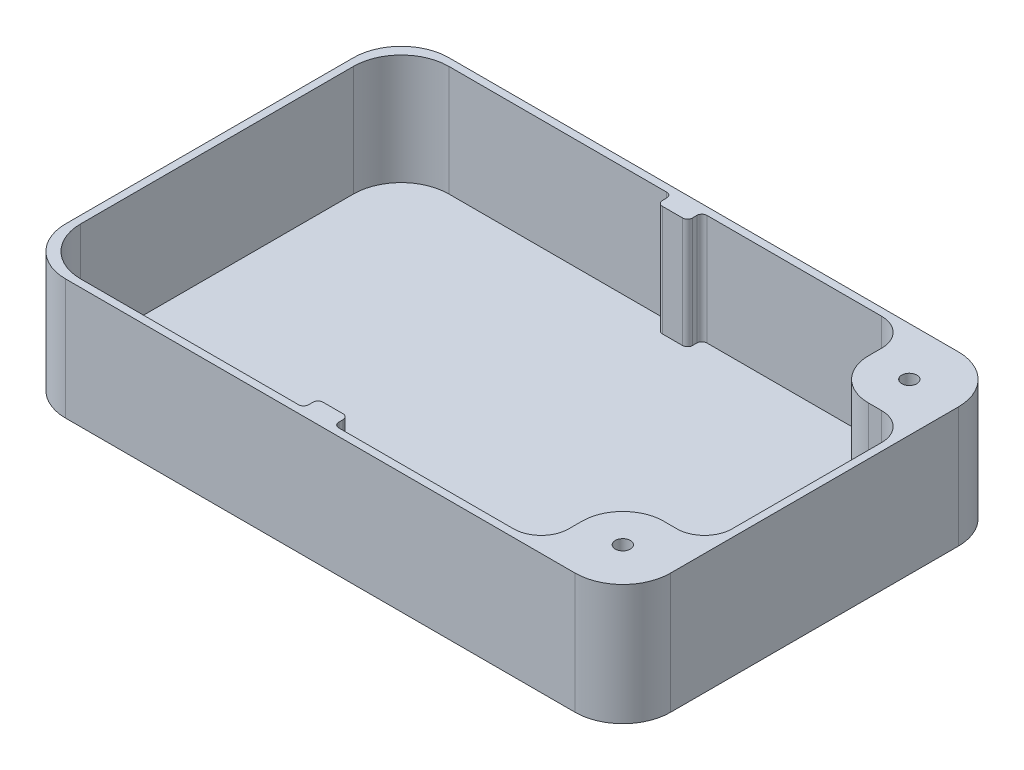
SolidWorks part; units mm, degrees
ref_plane "Front Plane" through (0, 0, 0) normal (0, 0, 1) x (1, 0, 0)
ref_plane "Top Plane" through (0, 0, 0) normal (0, 1, 0) x (1, 0, 0)
ref_plane "Right Plane" through (0, 0, 0) normal (1, 0, 0) x (0, 0, -1)
sketch "Sketch1" plane through (0, 0, 0) normal (0, 1, 0) x (1, 0, 0)
  line L1 (-60.2, 38.14) -> (60.2, 38.14)
  line L2 (-60.2, 38.14) -> (-60.2, -38.14)
  line L3 (-60.2, -38.14) -> (60.2, -38.14)
  line L4 (60.2, 38.14) -> (60.2, -38.14)
  line L5 (-60.2, 38.14) -> (60.2, -38.14) construction
  line L6 (-60.2, -38.14) -> (60.2, 38.14) construction
  point P0 (0, 0)
  dimension "D1" = 76.28
  dimension "D2" = 120.4
extrude "Boss-Extrude1" add sketch "Sketch1" along normal blind 24
sketch "Sketch2" plane through (0, 24, 0) normal (0, 1, 0) x (1, 0, 0)
  line L0 (60.2, -38.14) -> (60.2, 38.14) construction
  line L1 (-49.2, 36.64) -> (-5.841, 36.64)
  line L2 (-58.7, 27.14) -> (-58.7, -27.14)
  line L3 (2.159, -36.64) -> (36.94, -36.64)
  line L4 (58.7, 14.88) -> (58.7, -14.88)
  line L5 (-58.7, 36.64) -> (56.5491, -35.2974) construction
  line L6 (-58.7, -36.64) -> (65.2491, 40.7279) construction
  line L7 (60.2, 38.14) -> (-60.2, 38.14) construction
  line L8 (-60.2, -38.14) -> (60.2, -38.14) construction
  line L9 (42.44, -28.51) -> (42.44, -31.14)
  line L10 (50.57, -20.38) -> (53.2, -20.38)
  line L11 (-58.7, 0) -> (60.2, 0) construction
  line L12 (50.57, 20.38) -> (53.2, 20.38)
  line L13 (42.44, 31.14) -> (42.44, 28.51)
  line L14 (-49.2, -36.64) -> (-5.841, -36.64)
  line L15 (-4.841, 35.64) -> (-4.841, 34.7727)
  line L16 (1.159, -35.64) -> (1.159, -34.7727)
  line L17 (0.159, -33.7727) -> (-3.841, -33.7727)
  line L18 (-4.841, -35.64) -> (-4.841, -34.7727)
  line L19 (0.159, 33.7727) -> (-3.841, 33.7727)
  line L20 (1.159, 35.64) -> (1.159, 34.7727)
  line L21 (2.159, 36.64) -> (36.94, 36.64)
  circle A0 centre (50.57, -28.51) radius 1.5
  arc A1 (50.57, -20.38) -> (42.44, -28.51) centre (50.57, -28.51) ccw
  arc A2 (58.7, -14.88) -> (53.2, -20.38) centre (53.2, -14.88) cw
  arc A3 (42.44, -31.14) -> (36.94, -36.64) centre (36.94, -31.14) cw
  circle A4 centre (50.57, 28.51) radius 1.5
  arc A5 (58.7, 14.88) -> (53.2, 20.38) centre (53.2, 14.88) ccw
  arc A6 (-3.841, -33.7727) -> (-4.841, -34.7727) centre (-3.841, -34.7727) ccw
  arc A7 (42.44, 31.14) -> (36.94, 36.64) centre (36.94, 31.14) ccw
  arc A8 (-58.7, 27.14) -> (-49.2, 36.64) centre (-49.2, 27.14) cw
  arc A9 (-58.7, -27.14) -> (-49.2, -36.64) centre (-49.2, -27.14) ccw
  arc A10 (0.159, -33.7727) -> (1.159, -34.7727) centre (0.159, -34.7727) cw
  arc A11 (1.159, -35.64) -> (2.159, -36.64) centre (2.159, -35.64) ccw
  arc A12 (-4.841, -35.64) -> (-5.841, -36.64) centre (-5.841, -35.64) cw
  arc A13 (50.57, 20.38) -> (42.44, 28.51) centre (50.57, 28.51) cw
  arc A14 (-4.841, 35.64) -> (-5.841, 36.64) centre (-5.841, 35.64) ccw
  arc A15 (1.159, 35.64) -> (2.159, 36.64) centre (2.159, 35.64) cw
  arc A16 (0.159, 33.7727) -> (1.159, 34.7727) centre (0.159, 34.7727) ccw
  arc A17 (-3.841, 33.7727) -> (-4.841, 34.7727) centre (-3.841, 34.7727) cw
  point P0 (0, 0)
  point P40 (0, -36.64)
  point P57 (-4.841, -36.64)
  point P58 (0, 0)
  point P67 (-4.841, 36.64)
  point P68 (0, 36.64)
  dimension "D3" = 3
  dimension "D6" = 5.5
  dimension "D7" = 5.5
  dimension "D8" = 117.4
  dimension "D9" = 9.5
  dimension "D10" = 1
  dimension "D11" = 1
  dimension "D12" = 1
  dimension "D1" = 1.5
  dimension "D2" = 1.5
  dimension "D4" = 9.63
  dimension "D5" = 9.63
  dimension "D13" = 4
fillet "Fillet1" radius 9.5 4 edges at (-60.2, 12, -38.14) (60.2, 12, -38.14) (60.2, 12, 38.14) (-60.2, 12, 38.14)
extrude "Cut-Extrude1" cut sketch "Sketch2" against normal blind 22
